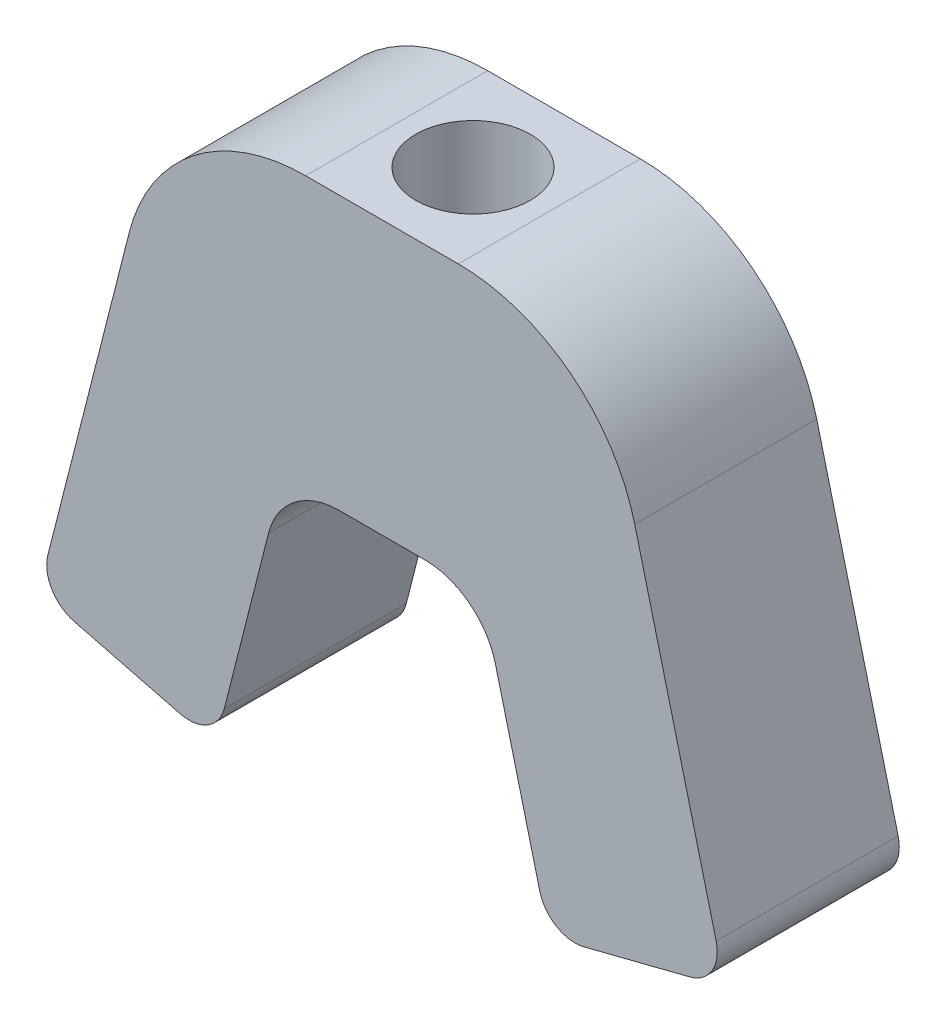
SolidWorks part; units mm, degrees
material "6061-T6 (SS)"
ref_plane "Front Plane" through (0, 0, 0) normal (0, 0, 1) x (1, 0, 0)
ref_plane "Top Plane" through (0, 0, 0) normal (0, 1, 0) x (1, 0, 0)
ref_plane "Right Plane" through (0, 0, 0) normal (1, 0, 0) x (0, 0, -1)
sketch "Sketch1" plane through (0, 0, 0) normal (0, 0, 1) x (1, 0, 0)
  line L0 (0, 0) -> (-19.3675, -76.2) construction
  line L1 (-19.3675, -76.2) -> (19.3675, -76.2) construction
  line L2 (19.3675, -76.2) -> (0, 0) construction
  line L3 (0, 0) -> (0, -76.2) construction
  line L4 (-11.9711, -34.2103) -> (-5.8167, -35.7745)
  line L5 (15.1754, -59.7064) -> (10.6223, -60.8637) construction
  line L6 (-5.8167, -35.7745) -> (-3.4704, -26.543)
  line L9 (5.8167, -35.7745) -> (11.9711, -34.2103)
  line L11 (11.9711, -34.2103) -> (7.6014, -17.018)
  line L12 (7.6014, -17.018) -> (-7.6014, -17.018)
  line L13 (-7.6014, -17.018) -> (-11.9711, -34.2103)
  line L15 (-3.4704, -26.543) -> (3.4704, -26.543)
  line L16 (3.4704, -26.543) -> (5.8167, -35.7745)
  dimension "D1" = 38.735
  dimension "D2" = 76.2
  dimension "D3" = 3.175
  dimension "D4" = 3.175
  dimension "D5" = 3.175
  dimension "D6" = 17.018
  dimension "D7" = 3.175
  dimension "D8" = 9.525
  dimension "D9" = 9.525
  dimension "D10" = 17.018
extrude "Boss-Extrude1" add sketch "Sketch1" along normal blind 6.35
fillet "Fillet1" radius 6.35 2 edges at (-7.6014, -17.018, 3.175) (7.6014, -17.018, 3.175)
fillet "Fillet2" radius 2.54 2 edges at (3.4704, -26.543, 3.175) (-3.4704, -26.543, 3.175)
fillet "Fillet3" radius 1.27 4 edges at (11.9711, -34.2103, 3.175) (5.8167, -35.7745, 3.175) (-5.8167, -35.7745, 3.175) (-11.9711, -34.2103, 3.175)
hole_wizard "#8-32 Tapped Hole3" positions "3DSketch1" profile "Sketch8" tap size "#8-32" standard "ANSI Inch"
sketch3d "3DSketch1"
  line L0 (-7.0476, -35.4616, 6.35) -> (-10.7402, -34.5231, 0) construction
  line L1 (10.7402, -34.5231, 6.35) -> (7.0476, -35.4616, 0) construction
  line L2 (2.6634, -17.018, 0) -> (-2.6634, -17.018, 6.35) construction
  point P0 (-8.8939, -34.9924, 3.175)
  point P8 (8.8939, -34.9924, 3.175)
  point P16 (0, -17.018, 3.175)
sketch "Sketch8" plane through (-8.8939, -34.9924, 3.175) normal (0, 0, 1) x (0.9692, -0.2463, 0)
  line L0 (0, 0) -> (0, 11.9104)
  line L1 (0, 11.9104) -> (2, 10.7086)
  line L2 (2, 10.7086) -> (2, 0)
  line L5 (2, 0) -> (0, 0)
  line L10 (0, 11.9104) -> (-2, 10.7086) construction
  line L11 (0, -6.35) -> (0, 107.95) construction
  dimension "Tap Drill Dia." = 4
  dimension "Tap Drill Depth" = 10.7086
  dimension "Drill Angle" = 118
cosmetic thread "Hole Thread3" parameters "D1"=8.3312, "D2"=4.1656
cosmetic thread "Hole Thread4" parameters "D1"=8.3312, "D2"=4.1656
cosmetic thread "Hole Thread5" parameters "D1"=8.3312, "D2"=4.1656
